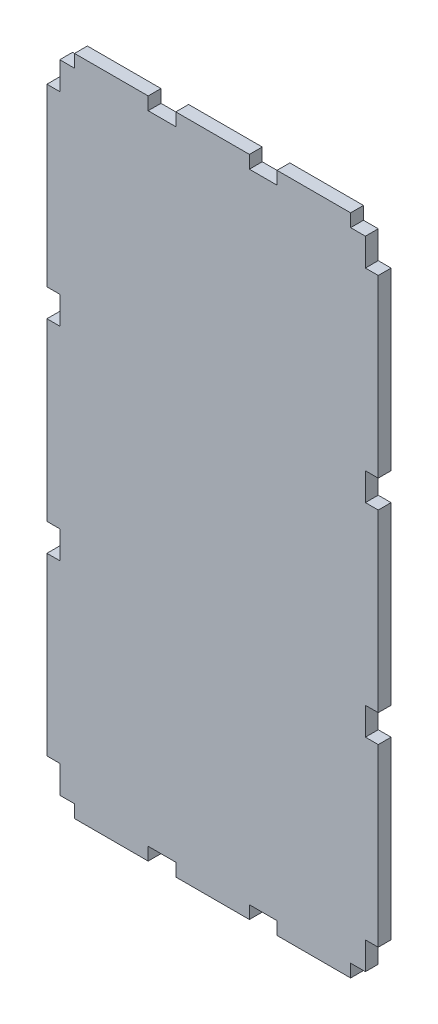
SolidWorks part; units mm, degrees
material "Oak"
ref_plane "Front Plane" through (0, 0, 0) normal (0, 0, 1) x (1, 0, 0)
ref_plane "Top Plane" through (0, 0, 0) normal (0, 1, 0) x (1, 0, 0)
ref_plane "Right Plane" through (0, 0, 0) normal (1, 0, 0) x (0, 0, -1)
sketch "Base_Sketch" plane through (0, 0, 0) normal (0, 0, 1) x (1, 0, 0)
  line L1 (-152.4, 304.8) -> (152.4, 304.8)
  line L2 (-152.4, 304.8) -> (-152.4, -304.8)
  line L3 (-152.4, -304.8) -> (152.4, -304.8)
  line L4 (152.4, 304.8) -> (152.4, -304.8)
  line L5 (-152.4, 304.8) -> (152.4, -304.8) construction
  line L6 (-152.4, -304.8) -> (152.4, 304.8) construction
  point P0 (0, 0)
extrude "Boss-Extrude1" add sketch "Base_Sketch" along normal blind 11.81
sketch "Joint_X" plane through (0, 0, 11.81) normal (0, 0, 1) x (1, 0, 0)
  line L1 (-152.4, -304.8) -> (-127, -304.8)
  line L2 (-152.4, -304.8) -> (-152.4, -292.99)
  line L3 (-152.4, -292.99) -> (-127, -292.99)
  line L4 (-127, -304.8) -> (-127, -292.99)
  point P5 (-127, -298.895)
  dimension "D1" = 11.81
  dimension "D2" = 25.4
extrude "Cut-Extrude1" cut sketch "Joint_X" against normal through all
pattern_linear "LPattern1" count 4 spacing 93.1333 along (1, 0, 0) of "Cut-Extrude1"
mirror "Mirror1" about plane through (0, 0, 0) normal (0, 1, 0) of "LPattern1", "Cut-Extrude1"
sketch "Joint_Y" plane through (0, 0, 11.81) normal (0, 0, 1) x (1, 0, 0)
  line L1 (-152.4, -292.99) -> (-140.59, -292.99)
  line L2 (-152.4, -292.99) -> (-152.4, -267.59)
  line L3 (-152.4, -267.59) -> (-140.59, -267.59)
  line L4 (-140.59, -292.99) -> (-140.59, -267.59)
  dimension "D1" = 11.81
  dimension "D2" = 25.4
extrude "Cut-Extrude2" cut sketch "Joint_Y" against normal through all
pattern_linear "LPattern3" count 4 spacing 186.86 along (0, 1, 0) of "Cut-Extrude2"
mirror "Mirror4" about plane through (0, 0, 0) normal (1, 0, 0) of "LPattern3", "Cut-Extrude2"
equation "\"Material_Thickness\"= \"Material_Thickness@Petrov.Assembly\""
equation "\"D1@Boss-Extrude1\"=\"Material_Thickness\""
equation "\"D1@Joint_X\" = \"Material_Thickness\""
equation "\"D1@Joint_Y\" = \"Material_Thickness\""
equation "\"Num_Joints\"= \"Num_Joints@Petrov.Assembly\""
equation "\"D1@LPattern1\"=\"Num_Joints\""
equation "\"D1@LPattern3\"=\"Num_Joints\""
equation "\"Joint_Size\"= \"Joint_Size@Petrov.Assembly\""
equation "\"D2@Joint_X\"=\"Joint_Size\""
equation "\"D2@Joint_Y\"=\"Joint_Size\""
